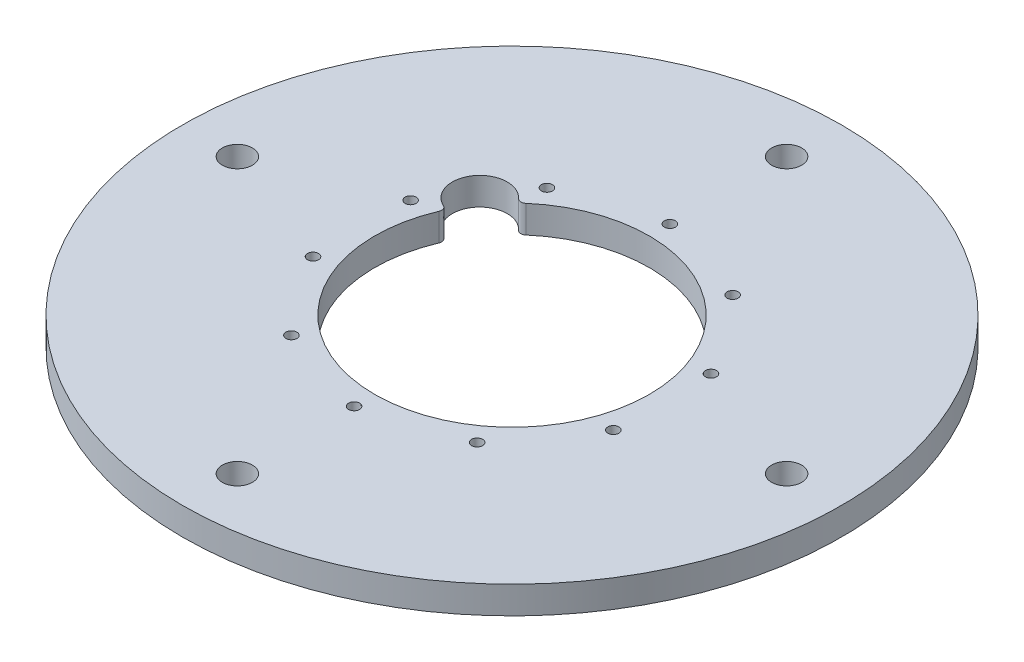
SolidWorks part; units mm, degrees
material "6061 Alloy"
ref_plane "Front Plane" through (0, 0, 0) normal (0, 0, 1) x (1, 0, 0)
ref_plane "Top Plane" through (0, 0, 0) normal (0, 1, 0) x (1, 0, 0)
ref_plane "Right Plane" through (0, 0, 0) normal (1, 0, 0) x (0, 0, -1)
sketch "Sketch1" plane through (0, 0, 0) normal (0, 1, 0) x (1, 0, 0)
  line L1 (0, 0) -> (0, 73.025) construction
  line L2 (0, 0) -> (0, 127) construction
  circle A3 centre (0, 0) radius 152.4
  circle A8 centre (0, 0) radius 127 construction
  circle A20 centre (0, 0) radius 63.5
  circle A23 centre (0, 0) radius 73.025 construction
  point P2 (0, 127)
  point P5 (0, 73.025)
  dimension "Diameter_Takeout_BoltCircle" = 254
  dimension "Diameter_ThrustPlate" = 304.8
  dimension "D2" = 146.05
  dimension "D4" = 127
  dimension "D1" = 0
extrude "ThrustPlate_TC3" add sketch "Sketch1" against normal blind 12.7 separate body
sketch "Sketch11" plane through (0, 0, 0) normal (0, 1, 0) x (1, 0, 0)
  point P0 (0, 127)
hole_wizard "UNDEF_Clearance_ThrustPlate" positions "Sketch11" profile "Sketch12" hole size "1/2" standard "ANSI Inch" end condition through all
sketch "Sketch12" plane through (0, 0, -127) normal (1, 0, 0) x (0, 0, 1)
  line L0 (0, 0) -> (0, 12.7)
  line L1 (0, 12.7) -> (6.9456, 12.7)
  line L2 (6.9456, 12.7) -> (6.9456, 0)
  line L5 (6.9456, 0) -> (0, 0)
  line L11 (0, -6.35) -> (0, 107.95) construction
  dimension "Thru Hole Dia." = 13.8913
  dimension "Thru Hole Depth" = 12.7
pattern_circular "Clearance_ThrustPlate_Pattern" count 4 over 360 about axis through (0, 0, 0) along (0, 1, 0) of "UNDEF_Clearance_ThrustPlate"
sketch "Sketch22" plane through (0, 0, 0) normal (0, 1, 0) x (1, 0, 0)
  point P0 (0, 73.025)
hole_wizard "#10 Clearance Hole1" positions "Sketch22" profile "Sketch23" hole size "#10" standard "ANSI Inch" end condition through all
sketch "Sketch23" plane through (0, 0, -73.025) normal (1, 0, 0) x (0, 0, 1)
  line L0 (0, 0) -> (0, 12.7)
  line L1 (0, 12.7) -> (2.5527, 12.7)
  line L2 (2.5527, 12.7) -> (2.5527, 0)
  line L5 (2.5527, 0) -> (0, 0)
  line L11 (0, -6.35) -> (0, 107.95) construction
  dimension "Thru Hole Dia." = 5.1054
  dimension "Thru Hole Depth" = 12.7
pattern_circular "CirPattern1" count 10 over 360 about axis through (0, 0, 0) along (0, 1, 0) of "#10 Clearance Hole1"
sketch "Sketch24" plane through (0, 0, 0) normal (0, 1, 0) x (1, 0, 0)
  line L0 (0, 0) -> (0, 152.4) construction
  line L1 (0, 0) -> (-123.2942, 89.5785) construction
  circle A0 centre (0, 0) radius 152.4 construction
  circle A1 centre (0, 0) radius 63.5 construction
  arc A3 (-45.1232, 48.1783) -> (-59.7641, 28.0268) centre (-54.4549, 39.5638) ccw
  arc A6 (-45.1232, 48.1783) -> (-41.5931, 47.9819) centre (-43.2569, 49.9012) ccw
  arc A7 (-41.5931, 47.9819) -> (-58.4865, 24.7302) centre (0, 0) ccw
  arc A8 (-59.7641, 28.0268) -> (-58.4865, 24.7302) centre (-60.8259, 25.7194) cw
  point P2 (-121.7419, 91.677)
  dimension "D2" = 12.7
  dimension "D4" = 2.54
  dimension "D1" = 67.31
  dimension "D3" = 54
extrude "Cut-Extrude1" cut sketch "Sketch24" against normal up to next
equation "\"Diameter_BackPlate\"= 6"
equation "\"VAR_Diameter_BackPlate_BoltCircle\"= 5.75"
equation "\"VAR_Diameter_FuelOuterPlenum\"= 4.4"
equation "\"Thickness_ThrustPlate\"= 0.5'undetermined"
equation "\"Diameter_ThrustPlate\"= 12'defined"
equation "\"Diameter_Takeout_BoltCicle\"= 10'defined"
equation "\"Diameter_Takeout_BoltCircle@Sketch1\"=\"Diameter_Takeout_BoltCicle\""
equation "\"Diameter_ThrustPlate@Sketch1\"=\"Diameter_ThrustPlate\""
equation "\"D1@ThrustPlate_TC3\"=\"Thickness_ThrustPlate\""
equation "\"VAR_Diameter_CBORE\"= 0.44'undetermined"
equation "\"VAR_Diameter_Clearance_ThrustPlate\"= 0.25'undetermined"
equation "\"NumberBolts_BackPlate\"= 20"
equation "\"NumberBolts_Takeout\"= 4'defined"
equation "\"D1@Clearance_ThrustPlate_Pattern\"=\"NumberBolts_Takeout\""
